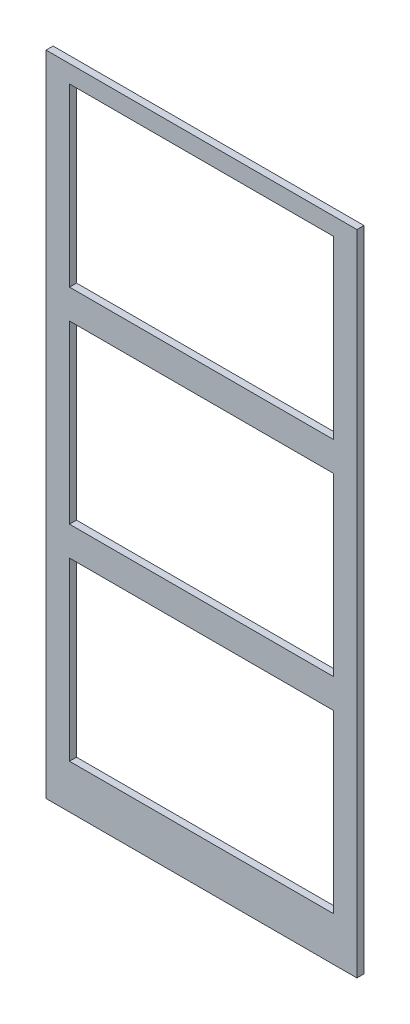
SolidWorks part; units mm, degrees
material "Carvalho"
ref_plane "Plano frontal" through (0, 0, 0) normal (0, 0, 1) x (1, 0, 0)
ref_plane "Plano superior" through (0, 0, 0) normal (0, 1, 0) x (1, 0, 0)
ref_plane "Plano direito" through (0, 0, 0) normal (1, 0, 0) x (0, 0, -1)
sketch "Esboço1" plane through (0, 0, 0) normal (0, 0, 1) x (1, 0, 0)
  line L0 (22.2503, 211.5774) -> (247.2503, 211.5774)
  line L5 (22.2503, 36.5774) -> (247.2503, 36.5774)
  line L6 (22.2503, 36.5774) -> (22.2503, 186.5774)
  line L7 (22.2503, 186.5774) -> (247.2503, 186.5774)
  line L8 (247.2503, 36.5774) -> (247.2503, 186.5774)
  line L9 (22.2503, 211.5774) -> (22.2503, 361.5774)
  line L10 (22.2503, 361.5774) -> (247.2503, 361.5774)
  line L11 (247.2503, 211.5774) -> (247.2503, 361.5774)
  line L12 (22.2503, 386.5774) -> (247.2503, 386.5774)
  line L13 (22.2503, 386.5774) -> (22.2503, 536.5774)
  line L14 (22.2503, 536.5774) -> (247.2503, 536.5774)
  line L15 (247.2503, 386.5774) -> (247.2503, 536.5774)
  line L16 (2.2503, -0.9226) -> (267.2503, -0.9226)
  line L17 (2.2503, -0.9226) -> (2.2503, 551.5774)
  line L18 (2.2503, 551.5774) -> (267.2503, 551.5774)
  line L19 (267.2503, -0.9226) -> (267.2503, 551.5774)
  dimension "D1" = 20
  dimension "D3" = 225
  dimension "D4" = 150
  dimension "D5" = 25
  dimension "D6" = 25
  dimension "D7" = 20
  dimension "D8" = 37.5
  dimension "D9" = 15
extrude "Ressalto-extrusão1" add sketch "Esboço1" along normal blind 6
